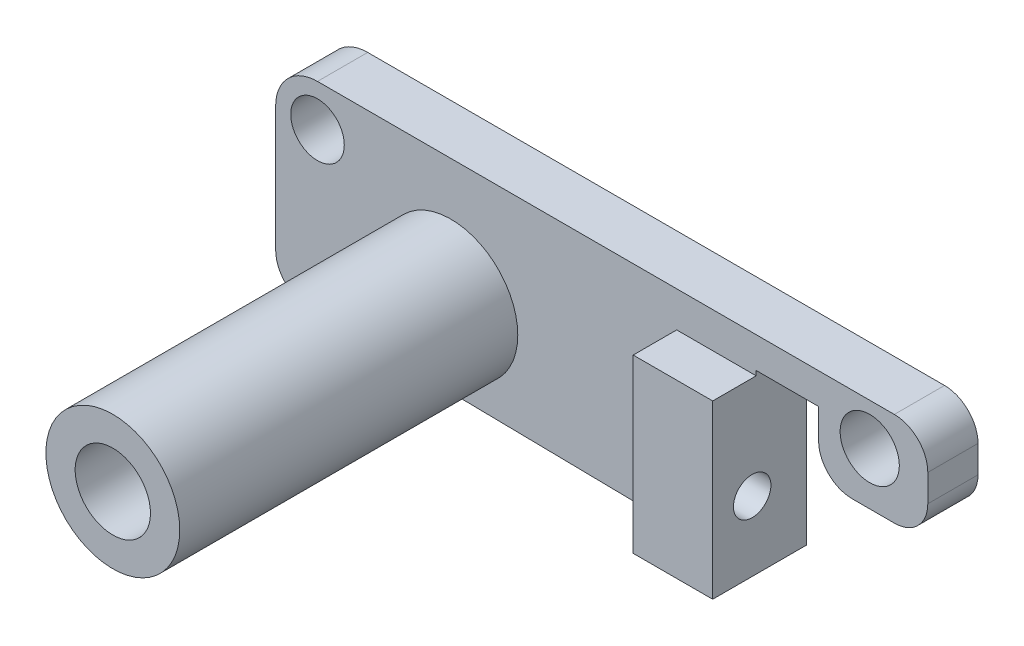
SolidWorks part; units mm, degrees
ref_plane "Front Plane" through (0, 0, 0) normal (0, 0, 1) x (1, 0, 0)
ref_plane "Top Plane" through (0, 0, 0) normal (0, 1, 0) x (1, 0, 0)
ref_plane "Right Plane" through (0, 0, 0) normal (1, 0, 0) x (0, 0, -1)
sketch "Sketch1" plane through (0, 0, 0) normal (0, 0, 1) x (1, 0, 0)
  line L0 (0, 2.5) -> (36.4706, 2.5)
  line L1 (36.4706, 2.5) -> (36.4706, -3.1248)
  line L2 (36.4706, -3.1248) -> (29.9452, -3.1248)
  line L3 (29.9452, -3.1248) -> (29.9452, 0.6474)
  line L5 (29.9452, 0.6474) -> (26.2164, 0.6474)
  line L7 (26.2164, 0.6474) -> (26.2164, -9.8934)
  line L8 (26.2164, -9.8934) -> (-2.5, -9.4475)
  line L9 (-2.5, -9.4475) -> (-2.5, 0)
  arc A0 (0, 2.5) -> (-2.5, 0) centre (0, 0) ccw
  circle A1 centre (0, 0) radius 1.6
  dimension "D1" = 3.2
  dimension "D2" = 5
extrude "Boss-Extrude1" add sketch "Sketch1" along normal blind 3
sketch "Sketch2" plane through (0, 0, 3) normal (0, 0, 1) x (1, 0, 0)
  line L0 (22.1, 0.3709) -> (18.05, 0.3709) construction
  line L1 (26.2164, -9.8934) -> (21.4651, -9.8934)
  line L2 (26.2164, -9.8934) -> (26.2164, 0.3709)
  line L3 (26.2164, 0.3709) -> (21.4651, 0.3709)
  line L4 (21.4651, -9.8934) -> (21.4651, 0.3709)
extrude "Boss-Extrude2" add sketch "Sketch2" along normal blind 2.6
sketch "Sketch3" plane through (26.2164, 0, 0) normal (1, 0, 0) x (0, 0, -1)
  circle A0 centre (-3.2412, -5.7291) radius 1.1187
extrude "Cut-Extrude1" cut sketch "Sketch3" against normal up to surface (4.7512 mm away) up to face at (21.4651, -5.7729, 4.04)
sketch "Sketch4" plane through (0, 0, 0) normal (0, 0, -1) x (-1, 0, 0)
  circle A0 centre (-33, 0) radius 1.7693
extrude "Cut-Extrude2" cut sketch "Sketch4" against normal blind 5
sketch "Sketch6" plane through (0, 0, 3) normal (0, 0, 1) x (1, 0, 0)
  circle A0 centre (7.968, -4.642) radius 4
  dimension "D2" = 8
extrude "Boss-Extrude3" add sketch "Sketch6" along normal blind 20.2
sketch "Sketch7" plane through (0, 0, 23.2) normal (0, 0, 1) x (1, 0, 0)
  circle A0 centre (7.968, -4.642) radius 2.25
  dimension "D1" = 4.5
extrude "Cut-Extrude3" cut sketch "Sketch7" against normal blind 8
fillet "Fillet1" radius 2 4 edges at (36.4706, 2.5, 1.5) (36.4706, -3.1248, 1.5) (29.9452, -3.1248, 1.5) (-2.5, -9.4475, 1.5)
